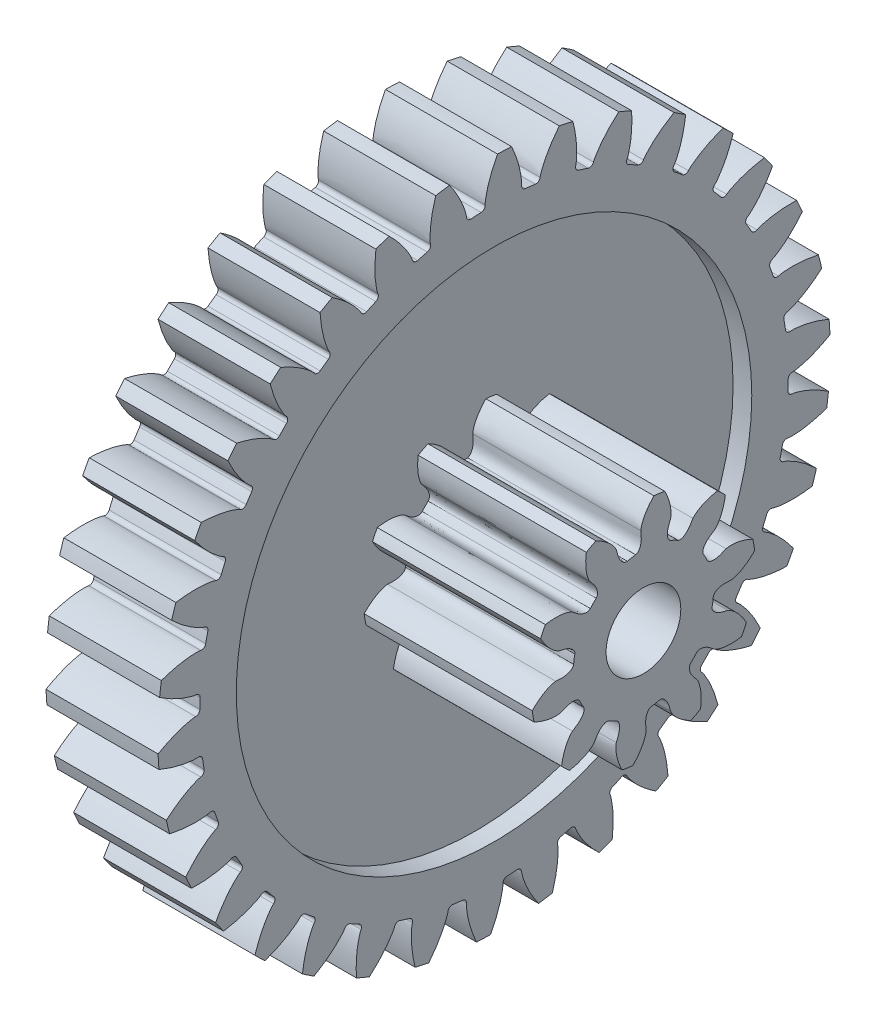
SolidWorks part; units mm, degrees
ref_plane "Plan de face" through (0, 0, 0) normal (0, 0, 1) x (1, 0, 0)
ref_plane "Plan de dessus" through (0, 0, 0) normal (0, 1, 0) x (1, 0, 0)
ref_plane "Plan de droite" through (0, 0, 0) normal (1, 0, 0) x (0, 0, -1)
sketch "Esquisse2" plane through (0, 0, 0) normal (1, 0, 0) x (0, 0, -1)
  arc A0 (8.9927, 0.363) -> (8.9699, 0.736) centre (0, 0) ccw
  arc A1 (8.7729, 2.0092) -> (8.6819, 2.3717) centre (0, 0) ccw
  arc A2 (8.2543, 3.587) -> (8.0983, 3.9266) centre (0, 0) ccw
  arc A3 (7.4547, 5.0426) -> (7.2389, 5.3478) centre (0, 0) ccw
  arc A4 (6.4012, 6.3266) -> (6.133, 6.5869) centre (0, 0) ccw
  arc A5 (5.1297, 7.395) -> (4.8182, 7.6016) centre (0, 0) ccw
  arc A6 (3.6835, 8.2117) -> (3.3394, 8.3575) centre (0, 0) ccw
  arc A7 (2.1119, 8.7487) -> (1.7468, 8.8289) centre (0, 0) ccw
  arc A8 (0.4683, 8.9878) -> (0.0948, 8.9995) centre (0, 0) ccw
  arc A9 (-1.1911, 8.9208) -> (-1.5605, 8.8637) centre (0, 0) ccw
  arc A10 (-2.8101, 8.5501) -> (-3.1626, 8.426) centre (0, 0) ccw
  arc A11 (-4.3333, 7.8881) -> (-4.657, 7.7014) centre (0, 0) ccw
  arc A12 (-5.7089, 6.9576) -> (-5.9929, 6.7146) centre (0, 0) ccw
  arc A13 (-6.8902, 5.7901) -> (-7.1246, 5.499) centre (0, 0) ccw
  arc A14 (-7.8368, 4.4254) -> (-8.0138, 4.0963) centre (0, 0) ccw
  arc A15 (-8.5165, 2.9101) -> (-8.63, 2.554) centre (0, 0) ccw
  arc A16 (-8.9063, 1.2956) -> (-8.9524, 0.9247) centre (0, 0) ccw
  arc A17 (-8.9927, -0.363) -> (-8.9699, -0.736) centre (0, 0) ccw
  arc A18 (-8.7729, -2.0092) -> (-8.6819, -2.3717) centre (0, 0) ccw
  arc A19 (-8.2543, -3.587) -> (-8.0983, -3.9266) centre (0, 0) ccw
  arc A20 (-7.4547, -5.0426) -> (-7.2389, -5.3478) centre (0, 0) ccw
  arc A21 (-6.4012, -6.3266) -> (-6.133, -6.5869) centre (0, 0) ccw
  arc A22 (-5.1297, -7.395) -> (-4.8182, -7.6016) centre (0, 0) ccw
  arc A23 (-3.6835, -8.2117) -> (-3.3394, -8.3575) centre (0, 0) ccw
  arc A24 (-2.1119, -8.7487) -> (-1.7468, -8.8289) centre (0, 0) ccw
  arc A25 (-0.4683, -8.9878) -> (-0.0948, -8.9995) centre (0, 0) ccw
  arc A26 (1.1911, -8.9208) -> (1.5605, -8.8637) centre (0, 0) ccw
  arc A27 (2.8101, -8.5501) -> (3.1626, -8.426) centre (0, 0) ccw
  arc A28 (4.3333, -7.8881) -> (4.657, -7.7014) centre (0, 0) ccw
  arc A29 (5.7089, -6.9576) -> (5.9929, -6.7146) centre (0, 0) ccw
  arc A30 (6.8902, -5.7901) -> (7.1246, -5.499) centre (0, 0) ccw
  arc A31 (7.8368, -4.4254) -> (8.0138, -4.0963) centre (0, 0) ccw
  arc A32 (8.5165, -2.9101) -> (8.63, -2.554) centre (0, 0) ccw
  arc A33 (8.9063, -1.2956) -> (8.9524, -0.9247) centre (0, 0) ccw
  arc A34 (7.987, 0) -> (7.8742, -0.1109) centre (7.9867, -0.1125) ccw
  arc A35 (7.8657, -0.3818) -> (7.9719, -0.4996) centre (7.9781, -0.3873) ccw
  arc A36 (7.8657, -0.3818) -> (7.8742, -0.1109) centre (0, 0) ccw
  arc A37 (7.851, 1.4676) -> (7.7605, 1.3379) centre (7.8714, 1.357) ccw
  arc A38 (7.802, 1.07) -> (7.928, 0.9737) centre (7.9134, 1.0853) ccw
  arc A39 (7.802, 1.07) -> (7.7605, 1.3379) centre (0, 0) ccw
  arc A40 (7.4477, 2.8852) -> (7.3826, 2.7411) centre (7.488, 2.7802) ccw
  arc A41 (7.4725, 2.4854) -> (7.6141, 2.4139) centre (7.5793, 2.5209) ccw
  arc A42 (7.4725, 2.4854) -> (7.3826, 2.7411) centre (0, 0) ccw
  arc A43 (6.7907, 4.2046) -> (6.7532, 4.0509) centre (6.8497, 4.1088) ccw
  arc A44 (6.8886, 3.8161) -> (7.0409, 3.7719) centre (6.987, 3.8706) ccw
  arc A45 (6.8886, 3.8161) -> (6.7532, 4.0509) centre (0, 0) ccw
  arc A46 (5.9025, 5.3808) -> (5.8938, 5.2229) centre (5.978, 5.2975) ccw
  arc A47 (6.0701, 5.0169) -> (6.2279, 5.0014) centre (6.1568, 5.0886) ccw
  arc A48 (6.0701, 5.0169) -> (5.8938, 5.2229) centre (0, 0) ccw
  arc A49 (4.8132, 6.3738) -> (4.8338, 6.2169) centre (4.9028, 6.3057) ccw
  arc A50 (5.0449, 6.0469) -> (5.2029, 6.0607) centre (5.117, 6.1333) ccw
  arc A51 (5.0449, 6.0469) -> (4.8338, 6.2169) centre (0, 0) ccw
  arc A52 (3.5601, 7.1497) -> (3.6091, 6.9993) centre (3.6607, 7.0993) ccw
  arc A53 (3.8479, 6.8709) -> (4.0007, 6.9135) centre (3.9028, 6.9691) ccw
  arc A54 (3.8479, 6.8709) -> (3.6091, 6.9993) centre (0, 0) ccw
  arc A55 (2.1857, 7.6821) -> (2.2616, 7.5433) centre (2.2939, 7.651) ccw
  arc A56 (2.5198, 7.461) -> (2.6622, 7.5309) centre (2.5558, 7.5676) ccw
  arc A57 (2.5198, 7.461) -> (2.2616, 7.5433) centre (0, 0) ccw
  arc A58 (0.7369, 7.9529) -> (0.837, 7.8304) centre (0.8489, 7.9423) ccw
  arc A59 (1.106, 7.797) -> (1.2331, 7.8918) centre (1.1218, 7.9083) ccw
  arc A60 (1.106, 7.797) -> (0.837, 7.8304) centre (0, 0) ccw
  arc A61 (-0.7369, 7.9529) -> (-0.6161, 7.8509) centre (-0.6249, 7.963) ccw
  arc A62 (-0.3455, 7.8674) -> (-0.2381, 7.984) centre (-0.3505, 7.9798) ccw
  arc A63 (-0.3455, 7.8674) -> (-0.6161, 7.8509) centre (0, 0) ccw
  arc A64 (-2.1857, 7.6821) -> (-2.0482, 7.604) centre (-2.0775, 7.7126) ccw
  arc A65 (-1.7853, 7.67) -> (-1.7011, 7.8044) centre (-1.8108, 7.7795) ccw
  arc A66 (-1.7853, 7.67) -> (-2.0482, 7.604) centre (0, 0) ccw
  arc A67 (-3.5601, 7.1497) -> (-3.4106, 7.0981) centre (-3.4593, 7.1996) ccw
  arc A68 (-3.1642, 7.2113) -> (-3.1062, 7.3589) centre (-3.2095, 7.3143) ccw
  arc A69 (-3.1642, 7.2113) -> (-3.4106, 7.0981) centre (0, 0) ccw
  arc A70 (-4.8132, 6.3738) -> (-4.6568, 6.3506) centre (-4.7233, 6.4413) ccw
  arc A71 (-4.4354, 6.5071) -> (-4.4055, 6.6628) centre (-4.4988, 6.6001) ccw
  arc A72 (-4.4354, 6.5071) -> (-4.6568, 6.3506) centre (0, 0) ccw
  arc A73 (-5.9025, 5.3808) -> (-5.7444, 5.3868) centre (-5.8265, 5.4637) ccw
  arc A74 (-5.5556, 5.5813) -> (-5.5547, 5.7399) centre (-5.635, 5.661) ccw
  arc A75 (-5.5556, 5.5813) -> (-5.7444, 5.3868) centre (0, 0) ccw
  arc A76 (-6.7907, 4.2046) -> (-6.6364, 4.2395) centre (-6.7312, 4.3001) ccw
  arc A77 (-6.4866, 4.4654) -> (-6.5149, 4.6215) centre (-6.5792, 4.5292) ccw
  arc A78 (-6.4866, 4.4654) -> (-6.6364, 4.2395) centre (0, 0) ccw
  arc A79 (-7.4477, 2.8852) -> (-7.3024, 2.9479) centre (-7.4067, 2.99) ccw
  arc A80 (-7.1966, 3.1975) -> (-7.2531, 3.3457) centre (-7.2995, 3.2432) ccw
  arc A81 (-7.1966, 3.1975) -> (-7.3024, 2.9479) centre (0, 0) ccw
  arc A82 (-7.851, 1.4676) -> (-7.7198, 1.5559) centre (-7.83, 1.5781) ccw
  arc A83 (-7.6616, 1.8207) -> (-7.7444, 1.956) centre (-7.7711, 1.8467) ccw
  arc A84 (-7.6616, 1.8207) -> (-7.7198, 1.5559) centre (0, 0) ccw
  arc A85 (-7.987, 0) -> (-7.8742, 0.1109) centre (-7.9867, 0.1125) ccw
  arc A86 (-7.8657, 0.3818) -> (-7.9719, 0.4996) centre (-7.9781, 0.3873) ccw
  arc A87 (-7.8657, 0.3818) -> (-7.8742, 0.1109) centre (0, 0) ccw
  arc A88 (-7.851, -1.4676) -> (-7.7605, -1.3379) centre (-7.8714, -1.357) ccw
  arc A89 (-7.802, -1.07) -> (-7.928, -0.9737) centre (-7.9134, -1.0853) ccw
  arc A90 (-7.802, -1.07) -> (-7.7605, -1.3379) centre (0, 0) ccw
  arc A91 (-7.4477, -2.8852) -> (-7.3826, -2.7411) centre (-7.488, -2.7802) ccw
  arc A92 (-7.4725, -2.4854) -> (-7.6141, -2.4139) centre (-7.5793, -2.5209) ccw
  arc A93 (-7.4725, -2.4854) -> (-7.3826, -2.7411) centre (0, 0) ccw
  arc A94 (-6.7907, -4.2046) -> (-6.7532, -4.0509) centre (-6.8497, -4.1088) ccw
  arc A95 (-6.8886, -3.8161) -> (-7.0409, -3.7719) centre (-6.987, -3.8706) ccw
  arc A96 (-6.8886, -3.8161) -> (-6.7532, -4.0509) centre (0, 0) ccw
  arc A97 (-5.9025, -5.3808) -> (-5.8938, -5.2229) centre (-5.978, -5.2975) ccw
  arc A98 (-6.0701, -5.0169) -> (-6.2279, -5.0014) centre (-6.1568, -5.0886) ccw
  arc A99 (-6.0701, -5.0169) -> (-5.8938, -5.2229) centre (0, 0) ccw
  arc A100 (-4.8132, -6.3738) -> (-4.8338, -6.2169) centre (-4.9028, -6.3057) ccw
  arc A101 (-5.0449, -6.0469) -> (-5.2029, -6.0607) centre (-5.117, -6.1333) ccw
  arc A102 (-5.0449, -6.0469) -> (-4.8338, -6.2169) centre (0, 0) ccw
  arc A103 (-3.5601, -7.1497) -> (-3.6091, -6.9993) centre (-3.6607, -7.0993) ccw
  arc A104 (-3.8479, -6.8709) -> (-4.0007, -6.9135) centre (-3.9028, -6.9691) ccw
  arc A105 (-3.8479, -6.8709) -> (-3.6091, -6.9993) centre (0, 0) ccw
  arc A106 (-2.1857, -7.6821) -> (-2.2616, -7.5433) centre (-2.2939, -7.651) ccw
  arc A107 (-2.5198, -7.461) -> (-2.6622, -7.5309) centre (-2.5558, -7.5676) ccw
  arc A108 (-2.5198, -7.461) -> (-2.2616, -7.5433) centre (0, 0) ccw
  arc A109 (-0.7369, -7.9529) -> (-0.837, -7.8304) centre (-0.8489, -7.9423) ccw
  arc A110 (-1.106, -7.797) -> (-1.2331, -7.8918) centre (-1.1218, -7.9083) ccw
  arc A111 (-1.106, -7.797) -> (-0.837, -7.8304) centre (0, 0) ccw
  arc A112 (0.7369, -7.9529) -> (0.6161, -7.8509) centre (0.6249, -7.963) ccw
  arc A113 (0.3455, -7.8674) -> (0.2381, -7.984) centre (0.3505, -7.9798) ccw
  arc A114 (0.3455, -7.8674) -> (0.6161, -7.8509) centre (0, 0) ccw
  arc A115 (2.1857, -7.6821) -> (2.0482, -7.604) centre (2.0775, -7.7126) ccw
  arc A116 (1.7853, -7.67) -> (1.7011, -7.8044) centre (1.8108, -7.7795) ccw
  arc A117 (1.7853, -7.67) -> (2.0482, -7.604) centre (0, 0) ccw
  arc A118 (3.5601, -7.1497) -> (3.4106, -7.0981) centre (3.4593, -7.1996) ccw
  arc A119 (3.1642, -7.2113) -> (3.1062, -7.3589) centre (3.2095, -7.3143) ccw
  arc A120 (3.1642, -7.2113) -> (3.4106, -7.0981) centre (0, 0) ccw
  arc A121 (4.8132, -6.3738) -> (4.6568, -6.3506) centre (4.7233, -6.4413) ccw
  arc A122 (4.4354, -6.5071) -> (4.4055, -6.6628) centre (4.4988, -6.6001) ccw
  arc A123 (4.4354, -6.5071) -> (4.6568, -6.3506) centre (0, 0) ccw
  arc A124 (5.9025, -5.3808) -> (5.7444, -5.3868) centre (5.8265, -5.4637) ccw
  arc A125 (5.5556, -5.5813) -> (5.5547, -5.7399) centre (5.635, -5.661) ccw
  arc A126 (5.5556, -5.5813) -> (5.7444, -5.3868) centre (0, 0) ccw
  arc A127 (6.7907, -4.2046) -> (6.6364, -4.2395) centre (6.7312, -4.3001) ccw
  arc A128 (6.4866, -4.4654) -> (6.5149, -4.6215) centre (6.5792, -4.5292) ccw
  arc A129 (6.4866, -4.4654) -> (6.6364, -4.2395) centre (0, 0) ccw
  arc A130 (7.4477, -2.8852) -> (7.3024, -2.9479) centre (7.4067, -2.99) ccw
  arc A131 (7.1966, -3.1975) -> (7.2531, -3.3457) centre (7.2995, -3.2432) ccw
  arc A132 (7.1966, -3.1975) -> (7.3024, -2.9479) centre (0, 0) ccw
  arc A133 (7.851, -1.4676) -> (7.7198, -1.5559) centre (7.83, -1.5781) ccw
  arc A134 (7.6616, -1.8207) -> (7.7444, -1.956) centre (7.7711, -1.8467) ccw
  arc A135 (7.6616, -1.8207) -> (7.7198, -1.5559) centre (0, 0) ccw
  circle A136 centre (0, 0) radius 1
  spline S0 degree 3 poles (7.987, 0) (8.0286, 0) (8.2037, 0.0282) (8.4818, 0.1115) (8.7713, 0.2415) (8.9323, 0.3284) (8.9927, 0.363) knots 0 0 0 0 0.124841 0.528779 0.867842 1.076016 1.076016 1.076016 1.076016
  spline S1 degree 3 poles (7.928, 0.9737) (7.9687, 0.9787) (8.146, 0.9721) (8.4321, 0.9233) (8.7354, 0.8295) (8.9058, 0.7629) (8.9699, 0.736) knots 0 0 0 0 0.124841 0.528779 0.867842 1.076016 1.076016 1.076016 1.076016
  spline S2 degree 3 poles (7.851, 1.4676) (7.8919, 1.4753) (8.0589, 1.5352) (8.3169, 1.6682) (8.5776, 1.8491) (8.7199, 1.9642) (8.7729, 2.0092) knots 0 0 0 0 0.124841 0.528779 0.867842 1.076016 1.076016 1.076016 1.076016
  spline S3 degree 3 poles (7.6141, 2.4139) (7.6532, 2.4263) (7.8287, 2.4523) (8.1189, 2.4569) (8.4342, 2.4205) (8.6139, 2.3863) (8.6819, 2.3717) knots 0 0 0 0 0.124841 0.528779 0.867842 1.076016 1.076016 1.076016 1.076016
  spline S4 degree 3 poles (7.4477, 2.8852) (7.4865, 2.9003) (7.6396, 2.9898) (7.8687, 3.168) (8.0918, 3.3938) (8.2105, 3.533) (8.2543, 3.587) knots 0 0 0 0 0.124841 0.528779 0.867842 1.076016 1.076016 1.076016 1.076016
  spline S5 degree 3 poles (7.0409, 3.7719) (7.0771, 3.7913) (7.2448, 3.8491) (7.5292, 3.9069) (7.8458, 3.9291) (8.0288, 3.9285) (8.0983, 3.9266) knots 0 0 0 0 0.124841 0.528779 0.867842 1.076016 1.076016 1.076016 1.076016
  spline S6 degree 3 poles (6.7907, 4.2046) (6.8261, 4.2265) (6.9601, 4.3427) (7.1526, 4.5599) (7.3304, 4.8229) (7.4215, 4.9815) (7.4547, 5.0426) knots 0 0 0 0 0.124841 0.528779 0.867842 1.076016 1.076016 1.076016 1.076016
  spline S7 degree 3 poles (6.2279, 5.0014) (6.2599, 5.0271) (6.4141, 5.1148) (6.6831, 5.2239) (6.9903, 5.3039) (7.1702, 5.3369) (7.2389, 5.3478) knots 0 0 0 0 0.124841 0.528779 0.867842 1.076016 1.076016 1.076016 1.076016
  spline S8 degree 3 poles (5.9025, 5.3808) (5.9332, 5.4088) (6.0436, 5.5477) (6.193, 5.7966) (6.3194, 6.0877) (6.3798, 6.2604) (6.4012, 6.3266) knots 0 0 0 0 0.124841 0.528779 0.867842 1.076016 1.076016 1.076016 1.076016
  spline S9 degree 3 poles (5.2029, 6.0607) (5.2296, 6.0918) (5.3651, 6.2063) (5.6094, 6.363) (5.8967, 6.498) (6.0675, 6.5636) (6.133, 6.5869) knots 0 0 0 0 0.124841 0.528779 0.867842 1.076016 1.076016 1.076016 1.076016
  spline S10 degree 3 poles (4.8132, 6.3738) (4.8383, 6.407) (4.9213, 6.5637) (5.0224, 6.8358) (5.0932, 7.1452) (5.1208, 7.3261) (5.1297, 7.395) knots 0 0 0 0 0.124841 0.528779 0.867842 1.076016 1.076016 1.076016 1.076016
  spline S11 degree 3 poles (4.0007, 6.9135) (4.0212, 6.949) (4.1333, 7.0864) (4.3447, 7.2854) (4.6022, 7.4709) (4.7581, 7.5667) (4.8182, 7.6016) knots 0 0 0 0 0.124841 0.528779 0.867842 1.076016 1.076016 1.076016 1.076016
  spline S12 degree 3 poles (3.5601, 7.1497) (3.5787, 7.1869) (3.6315, 7.3563) (3.6808, 7.6423) (3.6935, 7.9594) (3.6875, 8.1423) (3.6835, 8.2117) knots 0 0 0 0 0.124841 0.528779 0.867842 1.076016 1.076016 1.076016 1.076016
  spline S13 degree 3 poles (2.6622, 7.5309) (2.6759, 7.5696) (2.7608, 7.7253) (2.932, 7.9596) (3.1511, 8.1893) (3.2867, 8.3122) (3.3394, 8.3575) knots 0 0 0 0 0.124841 0.528779 0.867842 1.076016 1.076016 1.076016 1.076016
  spline S14 degree 3 poles (2.1857, 7.6821) (2.1971, 7.7221) (2.2179, 7.8983) (2.2139, 8.1885) (2.1681, 8.5026) (2.1286, 8.6812) (2.1119, 8.7487) knots 0 0 0 0 0.124841 0.528779 0.867842 1.076016 1.076016 1.076016 1.076016
  spline S15 degree 3 poles (1.2331, 7.8918) (1.2394, 7.9324) (1.2943, 8.101) (1.4195, 8.3629) (1.5927, 8.6289) (1.7034, 8.7746) (1.7468, 8.8289) knots 0 0 0 0 0.124841 0.528779 0.867842 1.076016 1.076016 1.076016 1.076016
  spline S16 degree 3 poles (0.7369, 7.9529) (0.7408, 7.9944) (0.7288, 8.1713) (0.6715, 8.4559) (0.5688, 8.7562) (0.4971, 8.9245) (0.4683, 8.9878) knots 0 0 0 0 0.124841 0.528779 0.867842 1.076016 1.076016 1.076016 1.076016
  spline S17 degree 3 poles (-0.2381, 7.984) (-0.2393, 8.025) (-0.2163, 8.2009) (-0.1413, 8.4813) (-0.02, 8.7746) (0.0621, 8.9382) (0.0948, 8.9995) knots 0 0 0 0 0.124841 0.528779 0.867842 1.076016 1.076016 1.076016 1.076016
  spline S18 degree 3 poles (-0.7369, 7.9529) (-0.7408, 7.9944) (-0.785, 8.1661) (-0.8937, 8.4353) (-1.0498, 8.7116) (-1.1512, 8.8639) (-1.1911, 8.9208) knots 0 0 0 0 0.124841 0.528779 0.867842 1.076016 1.076016 1.076016 1.076016
  spline S19 degree 3 poles (-1.7011, 7.8044) (-1.7098, 7.8444) (-1.7195, 8.0216) (-1.6973, 8.311) (-1.632, 8.6216) (-1.5814, 8.7974) (-1.5605, 8.8637) knots 0 0 0 0 0.124841 0.528779 0.867842 1.076016 1.076016 1.076016 1.076016
  spline S20 degree 3 poles (-2.1857, 7.6821) (-2.1971, 7.7221) (-2.2722, 7.8828) (-2.4284, 8.1275) (-2.6327, 8.3704) (-2.7603, 8.5015) (-2.8101, 8.5501) knots 0 0 0 0 0.124841 0.528779 0.867842 1.076016 1.076016 1.076016 1.076016
  spline S21 degree 3 poles (-3.1062, 7.3589) (-3.1221, 7.3967) (-3.1642, 7.569) (-3.1956, 7.8576) (-3.1884, 8.1749) (-3.171, 8.357) (-3.1626, 8.426) knots 0 0 0 0 0.124841 0.528779 0.867842 1.076016 1.076016 1.076016 1.076016
  spline S22 degree 3 poles (-3.5601, 7.1497) (-3.5787, 7.1869) (-3.682, 7.3311) (-3.8805, 7.5429) (-4.1259, 7.7441) (-4.2755, 7.8495) (-4.3333, 7.8881) knots 0 0 0 0 0.124841 0.528779 0.867842 1.076016 1.076016 1.076016 1.076016
  spline S23 degree 3 poles (-4.4055, 6.6628) (-4.4281, 6.6971) (-4.5011, 6.8587) (-4.585, 7.1366) (-4.6363, 7.4498) (-4.6526, 7.6321) (-4.657, 7.7014) knots 0 0 0 0 0.124841 0.528779 0.867842 1.076016 1.076016 1.076016 1.076016
  spline S24 degree 3 poles (-4.8132, 6.3738) (-4.8383, 6.407) (-4.9664, 6.5297) (-5.2004, 6.7014) (-5.4787, 6.8541) (-5.645, 6.9302) (-5.7089, 6.9576) knots 0 0 0 0 0.124841 0.528779 0.867842 1.076016 1.076016 1.076016 1.076016
  spline S25 degree 3 poles (-5.5547, 5.7399) (-5.5833, 5.7694) (-5.6848, 5.9148) (-5.8183, 6.1726) (-5.9262, 6.4711) (-5.9757, 6.6472) (-5.9929, 6.7146) knots 0 0 0 0 0.124841 0.528779 0.867842 1.076016 1.076016 1.076016 1.076016
  spline S26 degree 3 poles (-5.9025, 5.3808) (-5.9332, 5.4088) (-6.0816, 5.506) (-6.3432, 5.6317) (-6.6448, 5.7307) (-6.8223, 5.775) (-6.8902, 5.7901) knots 0 0 0 0 0.124841 0.528779 0.867842 1.076016 1.076016 1.076016 1.076016
  spline S27 degree 3 poles (-6.5149, 4.6215) (-6.5483, 4.6452) (-6.6748, 4.7696) (-6.8534, 4.9984) (-7.0144, 5.2719) (-7.0954, 5.436) (-7.1246, 5.499) knots 0 0 0 0 0.124841 0.528779 0.867842 1.076016 1.076016 1.076016 1.076016
  spline S28 degree 3 poles (-6.7907, 4.2046) (-6.8261, 4.2265) (-6.9898, 4.2947) (-7.2701, 4.3703) (-7.5847, 4.4122) (-7.7673, 4.423) (-7.8368, 4.4254) knots 0 0 0 0 0.124841 0.528779 0.867842 1.076016 1.076016 1.076016 1.076016
  spline S29 degree 3 poles (-7.2531, 3.3457) (-7.2904, 3.3629) (-7.4376, 3.4619) (-7.6552, 3.654) (-7.8637, 3.8933) (-7.9735, 4.0396) (-8.0138, 4.0963) knots 0 0 0 0 0.124841 0.528779 0.867842 1.076016 1.076016 1.076016 1.076016
  spline S30 degree 3 poles (-7.4477, 2.8852) (-7.4865, 2.9003) (-7.66, 2.9372) (-7.9493, 2.96) (-8.2663, 2.9434) (-8.4478, 2.9205) (-8.5165, 2.9101) knots 0 0 0 0 0.124841 0.528779 0.867842 1.076016 1.076016 1.076016 1.076016
  spline S31 degree 3 poles (-7.7444, 1.956) (-7.7842, 1.966) (-7.9471, 2.0363) (-8.1962, 2.1851) (-8.4452, 2.3821) (-8.58, 2.5057) (-8.63, 2.554) knots 0 0 0 0 0.124841 0.528779 0.867842 1.076016 1.076016 1.076016 1.076016
  spline S32 degree 3 poles (-7.851, 1.4676) (-7.8919, 1.4753) (-8.0692, 1.4797) (-8.3578, 1.4489) (-8.6664, 1.3743) (-8.8406, 1.3185) (-8.9063, 1.2956) knots 0 0 0 0 0.124841 0.528779 0.867842 1.076016 1.076016 1.076016 1.076016
  spline S33 degree 3 poles (-7.9719, 0.4996) (-8.0129, 0.5022) (-8.1859, 0.5413) (-8.4582, 0.6419) (-8.7391, 0.7897) (-8.8943, 0.8865) (-8.9524, 0.9247) knots 0 0 0 0 0.124841 0.528779 0.867842 1.076016 1.076016 1.076016 1.076016
  spline S34 degree 3 poles (-7.987, 0) (-8.0286, 0) (-8.2037, -0.0282) (-8.4818, -0.1115) (-8.7713, -0.2415) (-8.9323, -0.3284) (-8.9927, -0.363) knots 0 0 0 0 0.124841 0.528779 0.867842 1.076016 1.076016 1.076016 1.076016
  spline S35 degree 3 poles (-7.928, -0.9737) (-7.9687, -0.9787) (-8.146, -0.9721) (-8.4321, -0.9233) (-8.7354, -0.8295) (-8.9058, -0.7629) (-8.9699, -0.736) knots 0 0 0 0 0.124841 0.528779 0.867842 1.076016 1.076016 1.076016 1.076016
  spline S36 degree 3 poles (-7.851, -1.4676) (-7.8919, -1.4753) (-8.0589, -1.5352) (-8.3169, -1.6682) (-8.5776, -1.8491) (-8.7199, -1.9642) (-8.7729, -2.0092) knots 0 0 0 0 0.124841 0.528779 0.867842 1.076016 1.076016 1.076016 1.076016
  spline S37 degree 3 poles (-7.6141, -2.4139) (-7.6532, -2.4263) (-7.8287, -2.4523) (-8.1189, -2.4569) (-8.4342, -2.4205) (-8.6139, -2.3863) (-8.6819, -2.3717) knots 0 0 0 0 0.124841 0.528779 0.867842 1.076016 1.076016 1.076016 1.076016
  spline S38 degree 3 poles (-7.4477, -2.8852) (-7.4865, -2.9003) (-7.6396, -2.9898) (-7.8687, -3.168) (-8.0918, -3.3938) (-8.2105, -3.533) (-8.2543, -3.587) knots 0 0 0 0 0.124841 0.528779 0.867842 1.076016 1.076016 1.076016 1.076016
  spline S39 degree 3 poles (-7.0409, -3.7719) (-7.0771, -3.7913) (-7.2448, -3.8491) (-7.5292, -3.9069) (-7.8458, -3.9291) (-8.0288, -3.9285) (-8.0983, -3.9266) knots 0 0 0 0 0.124841 0.528779 0.867842 1.076016 1.076016 1.076016 1.076016
  spline S40 degree 3 poles (-6.7907, -4.2046) (-6.8261, -4.2265) (-6.9601, -4.3427) (-7.1526, -4.5599) (-7.3304, -4.8229) (-7.4215, -4.9815) (-7.4547, -5.0426) knots 0 0 0 0 0.124841 0.528779 0.867842 1.076016 1.076016 1.076016 1.076016
  spline S41 degree 3 poles (-6.2279, -5.0014) (-6.2599, -5.0271) (-6.4141, -5.1148) (-6.6831, -5.2239) (-6.9903, -5.3039) (-7.1702, -5.3369) (-7.2389, -5.3478) knots 0 0 0 0 0.124841 0.528779 0.867842 1.076016 1.076016 1.076016 1.076016
  spline S42 degree 3 poles (-5.9025, -5.3808) (-5.9332, -5.4088) (-6.0436, -5.5477) (-6.193, -5.7966) (-6.3194, -6.0877) (-6.3798, -6.2604) (-6.4012, -6.3266) knots 0 0 0 0 0.124841 0.528779 0.867842 1.076016 1.076016 1.076016 1.076016
  spline S43 degree 3 poles (-5.2029, -6.0607) (-5.2296, -6.0918) (-5.3651, -6.2063) (-5.6094, -6.363) (-5.8967, -6.498) (-6.0675, -6.5636) (-6.133, -6.5869) knots 0 0 0 0 0.124841 0.528779 0.867842 1.076016 1.076016 1.076016 1.076016
  spline S44 degree 3 poles (-4.8132, -6.3738) (-4.8383, -6.407) (-4.9213, -6.5637) (-5.0224, -6.8358) (-5.0932, -7.1452) (-5.1208, -7.3261) (-5.1297, -7.395) knots 0 0 0 0 0.124841 0.528779 0.867842 1.076016 1.076016 1.076016 1.076016
  spline S45 degree 3 poles (-4.0007, -6.9135) (-4.0212, -6.949) (-4.1333, -7.0864) (-4.3447, -7.2854) (-4.6022, -7.4709) (-4.7581, -7.5667) (-4.8182, -7.6016) knots 0 0 0 0 0.124841 0.528779 0.867842 1.076016 1.076016 1.076016 1.076016
  spline S46 degree 3 poles (-3.5601, -7.1497) (-3.5787, -7.1869) (-3.6315, -7.3563) (-3.6808, -7.6423) (-3.6935, -7.9594) (-3.6875, -8.1423) (-3.6835, -8.2117) knots 0 0 0 0 0.124841 0.528779 0.867842 1.076016 1.076016 1.076016 1.076016
  spline S47 degree 3 poles (-2.6622, -7.5309) (-2.6759, -7.5696) (-2.7608, -7.7253) (-2.932, -7.9596) (-3.1511, -8.1893) (-3.2867, -8.3122) (-3.3394, -8.3575) knots 0 0 0 0 0.124841 0.528779 0.867842 1.076016 1.076016 1.076016 1.076016
  spline S48 degree 3 poles (-2.1857, -7.6821) (-2.1971, -7.7221) (-2.2179, -7.8983) (-2.2139, -8.1885) (-2.1681, -8.5026) (-2.1286, -8.6812) (-2.1119, -8.7487) knots 0 0 0 0 0.124841 0.528779 0.867842 1.076016 1.076016 1.076016 1.076016
  spline S49 degree 3 poles (-1.2331, -7.8918) (-1.2394, -7.9324) (-1.2943, -8.101) (-1.4195, -8.3629) (-1.5927, -8.6289) (-1.7034, -8.7746) (-1.7468, -8.8289) knots 0 0 0 0 0.124841 0.528779 0.867842 1.076016 1.076016 1.076016 1.076016
  spline S50 degree 3 poles (-0.7369, -7.9529) (-0.7408, -7.9944) (-0.7288, -8.1713) (-0.6715, -8.4559) (-0.5688, -8.7562) (-0.4971, -8.9245) (-0.4683, -8.9878) knots 0 0 0 0 0.124841 0.528779 0.867842 1.076016 1.076016 1.076016 1.076016
  spline S51 degree 3 poles (0.2381, -7.984) (0.2393, -8.025) (0.2163, -8.2009) (0.1413, -8.4813) (0.02, -8.7746) (-0.0621, -8.9382) (-0.0948, -8.9995) knots 0 0 0 0 0.124841 0.528779 0.867842 1.076016 1.076016 1.076016 1.076016
  spline S52 degree 3 poles (0.7369, -7.9529) (0.7408, -7.9944) (0.785, -8.1661) (0.8937, -8.4353) (1.0498, -8.7116) (1.1512, -8.8639) (1.1911, -8.9208) knots 0 0 0 0 0.124841 0.528779 0.867842 1.076016 1.076016 1.076016 1.076016
  spline S53 degree 3 poles (1.7011, -7.8044) (1.7098, -7.8444) (1.7195, -8.0216) (1.6973, -8.311) (1.632, -8.6216) (1.5814, -8.7974) (1.5605, -8.8637) knots 0 0 0 0 0.124841 0.528779 0.867842 1.076016 1.076016 1.076016 1.076016
  spline S54 degree 3 poles (2.1857, -7.6821) (2.1971, -7.7221) (2.2722, -7.8828) (2.4284, -8.1275) (2.6327, -8.3704) (2.7603, -8.5015) (2.8101, -8.5501) knots 0 0 0 0 0.124841 0.528779 0.867842 1.076016 1.076016 1.076016 1.076016
  spline S55 degree 3 poles (3.1062, -7.3589) (3.1221, -7.3967) (3.1642, -7.569) (3.1956, -7.8576) (3.1884, -8.1749) (3.171, -8.357) (3.1626, -8.426) knots 0 0 0 0 0.124841 0.528779 0.867842 1.076016 1.076016 1.076016 1.076016
  spline S56 degree 3 poles (3.5601, -7.1497) (3.5787, -7.1869) (3.682, -7.3311) (3.8805, -7.5429) (4.1259, -7.7441) (4.2755, -7.8495) (4.3333, -7.8881) knots 0 0 0 0 0.124841 0.528779 0.867842 1.076016 1.076016 1.076016 1.076016
  spline S57 degree 3 poles (4.4055, -6.6628) (4.4281, -6.6971) (4.5011, -6.8587) (4.585, -7.1366) (4.6363, -7.4498) (4.6526, -7.6321) (4.657, -7.7014) knots 0 0 0 0 0.124841 0.528779 0.867842 1.076016 1.076016 1.076016 1.076016
  spline S58 degree 3 poles (4.8132, -6.3738) (4.8383, -6.407) (4.9664, -6.5297) (5.2004, -6.7014) (5.4787, -6.8541) (5.645, -6.9302) (5.7089, -6.9576) knots 0 0 0 0 0.124841 0.528779 0.867842 1.076016 1.076016 1.076016 1.076016
  spline S59 degree 3 poles (5.5547, -5.7399) (5.5833, -5.7694) (5.6848, -5.9148) (5.8183, -6.1726) (5.9262, -6.4711) (5.9757, -6.6472) (5.9929, -6.7146) knots 0 0 0 0 0.124841 0.528779 0.867842 1.076016 1.076016 1.076016 1.076016
  spline S60 degree 3 poles (5.9025, -5.3808) (5.9332, -5.4088) (6.0816, -5.506) (6.3432, -5.6317) (6.6448, -5.7307) (6.8223, -5.775) (6.8902, -5.7901) knots 0 0 0 0 0.124841 0.528779 0.867842 1.076016 1.076016 1.076016 1.076016
  spline S61 degree 3 poles (6.5149, -4.6215) (6.5483, -4.6452) (6.6748, -4.7696) (6.8534, -4.9984) (7.0144, -5.2719) (7.0954, -5.436) (7.1246, -5.499) knots 0 0 0 0 0.124841 0.528779 0.867842 1.076016 1.076016 1.076016 1.076016
  spline S62 degree 3 poles (6.7907, -4.2046) (6.8261, -4.2265) (6.9898, -4.2947) (7.2701, -4.3703) (7.5847, -4.4122) (7.7673, -4.423) (7.8368, -4.4254) knots 0 0 0 0 0.124841 0.528779 0.867842 1.076016 1.076016 1.076016 1.076016
  spline S63 degree 3 poles (7.2531, -3.3457) (7.2904, -3.3629) (7.4376, -3.4619) (7.6552, -3.654) (7.8637, -3.8933) (7.9735, -4.0396) (8.0138, -4.0963) knots 0 0 0 0 0.124841 0.528779 0.867842 1.076016 1.076016 1.076016 1.076016
  spline S64 degree 3 poles (7.4477, -2.8852) (7.4865, -2.9003) (7.66, -2.9372) (7.9493, -2.96) (8.2663, -2.9434) (8.4478, -2.9205) (8.5165, -2.9101) knots 0 0 0 0 0.124841 0.528779 0.867842 1.076016 1.076016 1.076016 1.076016
  spline S65 degree 3 poles (7.7444, -1.956) (7.7842, -1.966) (7.9471, -2.0363) (8.1962, -2.1851) (8.4452, -2.3821) (8.58, -2.5057) (8.63, -2.554) knots 0 0 0 0 0.124841 0.528779 0.867842 1.076016 1.076016 1.076016 1.076016
  spline S66 degree 3 poles (7.851, -1.4676) (7.8919, -1.4753) (8.0692, -1.4797) (8.3578, -1.4489) (8.6664, -1.3743) (8.8406, -1.3185) (8.9063, -1.2956) knots 0 0 0 0 0.124841 0.528779 0.867842 1.076016 1.076016 1.076016 1.076016
  spline S67 degree 3 poles (7.9719, -0.4996) (8.0129, -0.5022) (8.1859, -0.5413) (8.4582, -0.6419) (8.7391, -0.7897) (8.8943, -0.8865) (8.9524, -0.9247) knots 0 0 0 0 0.124841 0.528779 0.867842 1.076016 1.076016 1.076016 1.076016
  dimension "D1" = 2
extrude "Boss.-Extru.1" add sketch "Esquisse2" along normal blind 3
sketch "Esquisse3" plane through (3, 0, 0) normal (1, 0, 0) x (0, 0, -1)
  circle A0 centre (0, 0) radius 6.9
  dimension "D1" = 13.8
extrude "Enlèv. mat.-Extru.1" cut sketch "Esquisse3" against normal blind 0.5
sketch "Esquisse4" plane through (2.5, 0, 0) normal (1, 0, 0) x (0, 0, -1)
  arc A0 (2.9773, 0.3683) -> (2.9271, 0.6573) centre (0, 0) ccw
  arc A1 (2.1922, 2.048) -> (1.9817, 2.2523) centre (0, 0) ccw
  arc A2 (0.5698, 2.9454) -> (0.2794, 2.987) centre (0, 0) ccw
  arc A3 (-1.2703, 2.7178) -> (-1.5297, 2.5807) centre (0, 0) ccw
  arc A4 (-2.6252, 1.4521) -> (-2.7544, 1.1887) centre (0, 0) ccw
  arc A5 (-2.9773, -0.3683) -> (-2.9271, -0.6573) centre (0, 0) ccw
  arc A6 (-2.1922, -2.048) -> (-1.9817, -2.2523) centre (0, 0) ccw
  arc A7 (-0.5698, -2.9454) -> (-0.2794, -2.987) centre (0, 0) ccw
  arc A8 (1.2703, -2.7178) -> (1.5297, -2.5807) centre (0, 0) ccw
  arc A9 (2.6252, -1.4521) -> (2.7544, -1.1887) centre (0, 0) ccw
  arc A10 (1.8368, -0.3764) -> (1.8687, -0.154) centre (0, 0) ccw
  arc A11 (1.7073, 0.7751) -> (1.6023, 0.9738) centre (0, 0) ccw
  arc A12 (0.9256, 1.6306) -> (0.7239, 1.7296) centre (0, 0) ccw
  arc A13 (-0.2096, 1.8632) -> (-0.431, 1.8248) centre (0, 0) ccw
  arc A14 (-1.2648, 1.3842) -> (-1.4213, 1.2229) centre (0, 0) ccw
  arc A15 (-1.8368, 0.3764) -> (-1.8687, 0.154) centre (0, 0) ccw
  arc A16 (-1.7073, -0.7751) -> (-1.6023, -0.9738) centre (0, 0) ccw
  arc A17 (-0.9256, -1.6306) -> (-0.7239, -1.7296) centre (0, 0) ccw
  arc A18 (0.2096, -1.8632) -> (0.431, -1.8248) centre (0, 0) ccw
  arc A19 (1.2648, -1.3842) -> (1.4213, -1.2229) centre (0, 0) ccw
  circle A20 centre (0, 0) radius 1
  spline S0 degree 3 poles (2.349, 0) (2.3611, 0) (2.4126, 0.0085) (2.4945, 0.0326) (2.6584, 0.1065) (2.823, 0.2207) (2.9394, 0.3292) (2.9773, 0.3683) knots 0 0 0 0 0.036251 0.155621 0.255291 0.575255 0.744085 0.744085 0.744085 0.744085
  spline S1 degree 3 poles (2.2114, 0.7921) (2.2228, 0.7962) (2.2741, 0.8056) (2.3594, 0.8105) (2.5386, 0.7962) (2.7321, 0.7442) (2.8782, 0.6813) (2.9271, 0.6573) knots 0 0 0 0 0.036251 0.155621 0.255291 0.575255 0.744085 0.744085 0.744085 0.744085
  spline S2 degree 3 poles (1.9004, 1.3807) (1.9102, 1.3878) (1.9469, 1.4249) (1.9989, 1.4926) (2.0881, 1.6487) (2.1541, 1.8379) (2.1845, 1.9941) (2.1922, 2.048) knots 0 0 0 0 0.036251 0.155621 0.255291 0.575255 0.744085 0.744085 0.744085 0.744085
  spline S3 degree 3 poles (1.3235, 1.9407) (1.3303, 1.9507) (1.3663, 1.9885) (1.4324, 2.0425) (1.5858, 2.1363) (1.7728, 2.2079) (1.9281, 2.243) (1.9817, 2.2523) knots 0 0 0 0 0.036251 0.155621 0.255291 0.575255 0.744085 0.744085 0.744085 0.744085
  spline S4 degree 3 poles (0.7259, 2.234) (0.7296, 2.2455) (0.7375, 2.2971) (0.7398, 2.3825) (0.7202, 2.5612) (0.6625, 2.753) (0.5952, 2.8973) (0.5698, 2.9454) knots 0 0 0 0 0.036251 0.155621 0.255291 0.575255 0.744085 0.744085 0.744085 0.744085
  spline S5 degree 3 poles (-0.07, 2.348) (-0.0704, 2.36) (-0.0634, 2.4118) (-0.0417, 2.4943) (0.0272, 2.6604) (0.1365, 2.8283) (0.2415, 2.9479) (0.2794, 2.987) knots 0 0 0 0 0.036251 0.155621 0.255291 0.575255 0.744085 0.744085 0.744085 0.744085
  spline S6 degree 3 poles (-0.7259, 2.234) (-0.7296, 2.2455) (-0.7536, 2.2919) (-0.8019, 2.3623) (-0.9228, 2.4954) (-1.0823, 2.6166) (-1.2215, 2.6938) (-1.2703, 2.7178) knots 0 0 0 0 0.036251 0.155621 0.255291 0.575255 0.744085 0.744085 0.744085 0.744085
  spline S7 degree 3 poles (-1.4367, 1.8584) (-1.4441, 1.8679) (-1.4689, 1.9139) (-1.4999, 1.9934) (-1.5417, 2.1683) (-1.552, 2.3684) (-1.5374, 2.5268) (-1.5297, 2.5807) knots 0 0 0 0 0.036251 0.155621 0.255291 0.575255 0.744085 0.744085 0.744085 0.744085
  spline S8 degree 3 poles (-1.9004, 1.3807) (-1.9102, 1.3878) (-1.9568, 1.4112) (-2.0373, 1.4398) (-2.2133, 1.4764) (-2.4136, 1.4808) (-2.5715, 1.4614) (-2.6252, 1.4521) knots 0 0 0 0 0.036251 0.155621 0.255291 0.575255 0.744085 0.744085 0.744085 0.744085
  spline S9 degree 3 poles (-2.2547, 0.659) (-2.2663, 0.6624) (-2.3133, 0.6849) (-2.3852, 0.7311) (-2.5218, 0.848) (-2.6477, 1.0038) (-2.729, 1.1406) (-2.7544, 1.1887) knots 0 0 0 0 0.036251 0.155621 0.255291 0.575255 0.744085 0.744085 0.744085 0.744085
  spline S10 degree 3 poles (-2.349, 0) (-2.3611, 0) (-2.4126, -0.0085) (-2.4945, -0.0326) (-2.6584, -0.1065) (-2.823, -0.2207) (-2.9394, -0.3292) (-2.9773, -0.3683) knots 0 0 0 0 0.036251 0.155621 0.255291 0.575255 0.744085 0.744085 0.744085 0.744085
  spline S11 degree 3 poles (-2.2114, -0.7921) (-2.2228, -0.7962) (-2.2741, -0.8056) (-2.3594, -0.8105) (-2.5386, -0.7962) (-2.7321, -0.7442) (-2.8782, -0.6813) (-2.9271, -0.6573) knots 0 0 0 0 0.036251 0.155621 0.255291 0.575255 0.744085 0.744085 0.744085 0.744085
  spline S12 degree 3 poles (-1.9004, -1.3807) (-1.9102, -1.3878) (-1.9469, -1.4249) (-1.9989, -1.4926) (-2.0881, -1.6487) (-2.1541, -1.8379) (-2.1845, -1.9941) (-2.1922, -2.048) knots 0 0 0 0 0.036251 0.155621 0.255291 0.575255 0.744085 0.744085 0.744085 0.744085
  spline S13 degree 3 poles (-1.3235, -1.9407) (-1.3303, -1.9507) (-1.3663, -1.9885) (-1.4324, -2.0425) (-1.5858, -2.1363) (-1.7728, -2.2079) (-1.9281, -2.243) (-1.9817, -2.2523) knots 0 0 0 0 0.036251 0.155621 0.255291 0.575255 0.744085 0.744085 0.744085 0.744085
  spline S14 degree 3 poles (-0.7259, -2.234) (-0.7296, -2.2455) (-0.7375, -2.2971) (-0.7398, -2.3825) (-0.7202, -2.5612) (-0.6625, -2.753) (-0.5952, -2.8973) (-0.5698, -2.9454) knots 0 0 0 0 0.036251 0.155621 0.255291 0.575255 0.744085 0.744085 0.744085 0.744085
  spline S15 degree 3 poles (0.07, -2.348) (0.0704, -2.36) (0.0634, -2.4118) (0.0417, -2.4943) (-0.0272, -2.6604) (-0.1365, -2.8283) (-0.2415, -2.9479) (-0.2794, -2.987) knots 0 0 0 0 0.036251 0.155621 0.255291 0.575255 0.744085 0.744085 0.744085 0.744085
  spline S16 degree 3 poles (0.7259, -2.234) (0.7296, -2.2455) (0.7536, -2.2919) (0.8019, -2.3623) (0.9228, -2.4954) (1.0823, -2.6166) (1.2215, -2.6938) (1.2703, -2.7178) knots 0 0 0 0 0.036251 0.155621 0.255291 0.575255 0.744085 0.744085 0.744085 0.744085
  spline S17 degree 3 poles (1.4367, -1.8584) (1.4441, -1.8679) (1.4689, -1.9139) (1.4999, -1.9934) (1.5417, -2.1683) (1.552, -2.3684) (1.5374, -2.5268) (1.5297, -2.5807) knots 0 0 0 0 0.036251 0.155621 0.255291 0.575255 0.744085 0.744085 0.744085 0.744085
  spline S18 degree 3 poles (1.9004, -1.3807) (1.9102, -1.3878) (1.9568, -1.4112) (2.0373, -1.4398) (2.2133, -1.4764) (2.4136, -1.4808) (2.5715, -1.4614) (2.6252, -1.4521) knots 0 0 0 0 0.036251 0.155621 0.255291 0.575255 0.744085 0.744085 0.744085 0.744085
  spline S19 degree 3 poles (2.2547, -0.659) (2.2663, -0.6624) (2.3133, -0.6849) (2.3852, -0.7311) (2.5218, -0.848) (2.6477, -1.0038) (2.729, -1.1406) (2.7544, -1.1887) knots 0 0 0 0 0.036251 0.155621 0.255291 0.575255 0.744085 0.744085 0.744085 0.744085
  spline S20 degree 3 poles (2.349, 0) (2.2648, 0) (2.1034, 0.0291) (1.8817, -0.0633) (1.8687, -0.154) knots 0 0 0 0 0.252618 0.527509 0.527509 0.527509 0.527509
  spline S21 degree 3 poles (2.2547, -0.659) (2.1739, -0.6353) (2.0108, -0.618) (1.8238, -0.4671) (1.8368, -0.3764) knots 0 0 0 0 0.252618 0.527509 0.527509 0.527509 0.527509
  spline S22 degree 3 poles (1.9004, 1.3807) (1.8323, 1.3312) (1.6846, 1.2599) (1.5595, 1.0548) (1.6023, 0.9738) knots 0 0 0 0 0.252618 0.527509 0.527509 0.527509 0.527509
  spline S23 degree 3 poles (2.2114, 0.7921) (2.1321, 0.7637) (1.99, 0.682) (1.7501, 0.6941) (1.7073, 0.7751) knots 0 0 0 0 0.252618 0.527509 0.527509 0.527509 0.527509
  spline S24 degree 3 poles (0.7259, 2.234) (0.6999, 2.1539) (0.6223, 2.0095) (0.6416, 1.77) (0.7239, 1.7296) knots 0 0 0 0 0.252618 0.527509 0.527509 0.527509 0.527509
  spline S25 degree 3 poles (1.3235, 1.9407) (1.276, 1.8711) (1.2091, 1.7214) (1.0079, 1.5902) (0.9256, 1.6306) knots 0 0 0 0 0.252618 0.527509 0.527509 0.527509 0.527509
  spline S26 degree 3 poles (-0.7259, 2.234) (-0.6999, 2.1539) (-0.6776, 1.9915) (-0.5213, 1.8091) (-0.431, 1.8248) knots 0 0 0 0 0.252618 0.527509 0.527509 0.527509 0.527509
  spline S27 degree 3 poles (-0.07, 2.348) (-0.0675, 2.2638) (-0.0336, 2.1034) (-0.1193, 1.8789) (-0.2096, 1.8632) knots 0 0 0 0 0.252618 0.527509 0.527509 0.527509 0.527509
  spline S28 degree 3 poles (-1.9004, 1.3807) (-1.8323, 1.3312) (-1.7188, 1.2128) (-1.4851, 1.1572) (-1.4213, 1.2229) knots 0 0 0 0 0.252618 0.527509 0.527509 0.527509 0.527509
  spline S29 degree 3 poles (-1.4367, 1.8584) (-1.3852, 1.7918) (-1.2635, 1.6819) (-1.2009, 1.4499) (-1.2648, 1.3842) knots 0 0 0 0 0.252618 0.527509 0.527509 0.527509 0.527509
  spline S30 degree 3 poles (-2.349, 0) (-2.2648, 0) (-2.1034, -0.0291) (-1.8817, 0.0633) (-1.8687, 0.154) knots 0 0 0 0 0.252618 0.527509 0.527509 0.527509 0.527509
  spline S31 degree 3 poles (-2.2547, 0.659) (-2.1739, 0.6353) (-2.0108, 0.618) (-1.8238, 0.4671) (-1.8368, 0.3764) knots 0 0 0 0 0.252618 0.527509 0.527509 0.527509 0.527509
  spline S32 degree 3 poles (-1.9004, -1.3807) (-1.8323, -1.3312) (-1.6846, -1.2599) (-1.5595, -1.0548) (-1.6023, -0.9738) knots 0 0 0 0 0.252618 0.527509 0.527509 0.527509 0.527509
  spline S33 degree 3 poles (-2.2114, -0.7921) (-2.1321, -0.7637) (-1.99, -0.682) (-1.7501, -0.6941) (-1.7073, -0.7751) knots 0 0 0 0 0.252618 0.527509 0.527509 0.527509 0.527509
  spline S34 degree 3 poles (-0.7259, -2.234) (-0.6999, -2.1539) (-0.6223, -2.0095) (-0.6416, -1.77) (-0.7239, -1.7296) knots 0 0 0 0 0.252618 0.527509 0.527509 0.527509 0.527509
  spline S35 degree 3 poles (-1.3235, -1.9407) (-1.276, -1.8711) (-1.2091, -1.7214) (-1.0079, -1.5902) (-0.9256, -1.6306) knots 0 0 0 0 0.252618 0.527509 0.527509 0.527509 0.527509
  spline S36 degree 3 poles (0.7259, -2.234) (0.6999, -2.1539) (0.6776, -1.9915) (0.5213, -1.8091) (0.431, -1.8248) knots 0 0 0 0 0.252618 0.527509 0.527509 0.527509 0.527509
  spline S37 degree 3 poles (0.07, -2.348) (0.0675, -2.2638) (0.0336, -2.1034) (0.1193, -1.8789) (0.2096, -1.8632) knots 0 0 0 0 0.252618 0.527509 0.527509 0.527509 0.527509
  spline S38 degree 3 poles (1.9004, -1.3807) (1.8323, -1.3312) (1.7188, -1.2128) (1.4851, -1.1572) (1.4213, -1.2229) knots 0 0 0 0 0.252618 0.527509 0.527509 0.527509 0.527509
  spline S39 degree 3 poles (1.4367, -1.8584) (1.3852, -1.7918) (1.2635, -1.6819) (1.2009, -1.4499) (1.2648, -1.3842) knots 0 0 0 0 0.252618 0.527509 0.527509 0.527509 0.527509
extrude "Boss.-Extru.2" add sketch "Esquisse4" along normal blind 4.5
